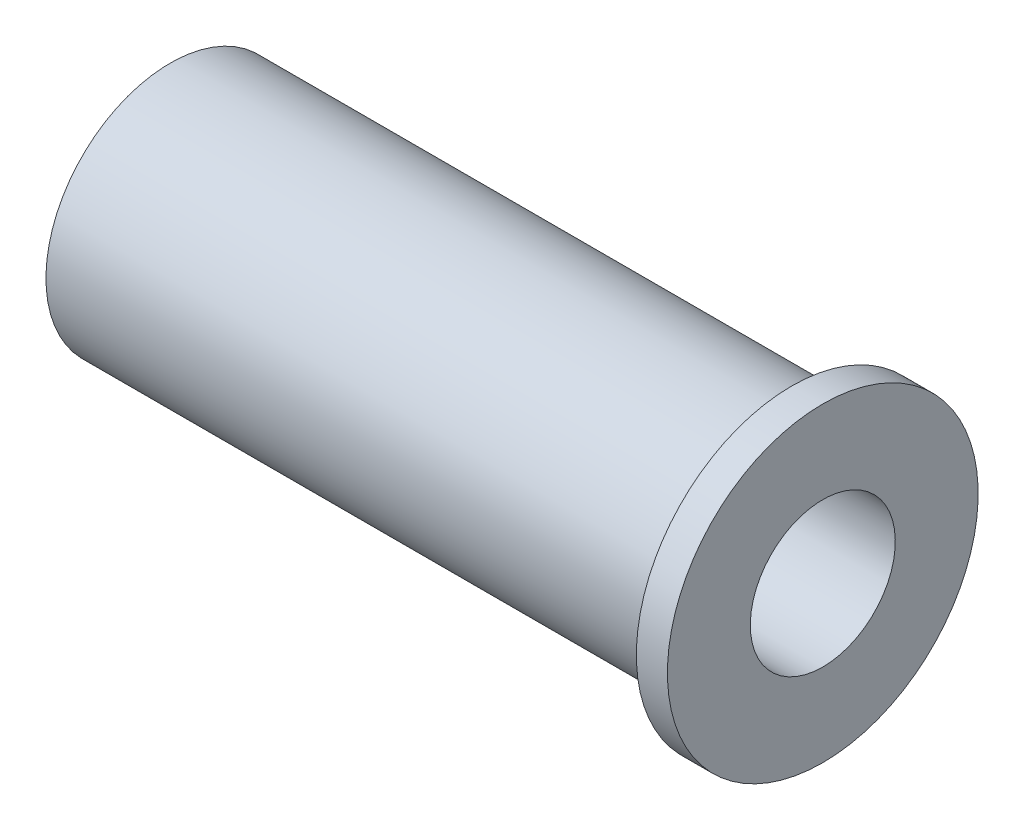
SolidWorks part; units mm, degrees
material "AISI 304"
ref_plane "Спереди" through (0, 0, 0) normal (0, 0, 1) x (1, 0, 0)
ref_plane "Сверху" through (0, 0, 0) normal (0, 1, 0) x (1, 0, 0)
ref_plane "Справа" through (0, 0, 0) normal (1, 0, 0) x (0, 0, -1)
other "Configuration Table"
sketch "Эскиз1" plane through (0, 0, 0) normal (0, 0, 1) x (1, 0, 0)
  line L0 (0, 0) -> (19, 0) construction
  line L1 (0, 7) -> (0, 12)
  line L2 (0, 12) -> (60, 12)
  line L3 (60, 12) -> (60, 15)
  line L4 (60, 15) -> (63, 15)
  line L5 (63, 15) -> (63, 7)
  line L6 (0, 7) -> (63, 7)
  line L7 (0, 7) -> (0, 0) construction
  line L8 (63, 8) -> (0, 8) construction
  dimension "D1" = 24
  dimension "D2" = 30
  dimension "D3" = 3
  dimension "D4" = 63
  dimension "D5" = 14
  dimension "D6" = 1
revolve "Повернуть1" add sketch "Эскиз1" angle 360 about L0
cosmetic thread "Условное изображение резьбы1" parameters "D2"=16
